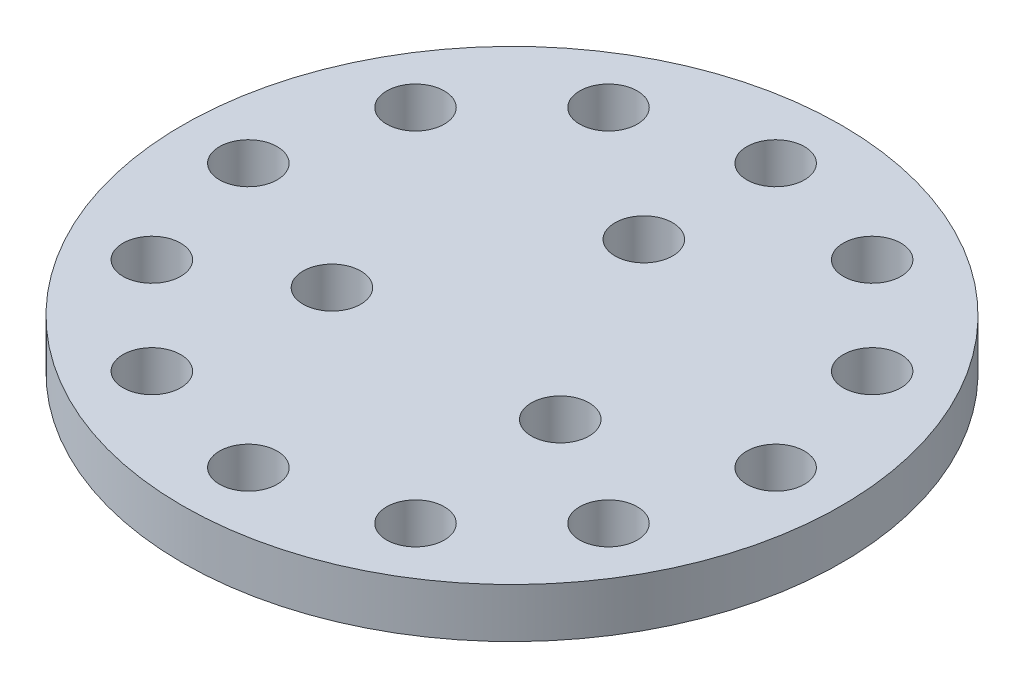
SolidWorks part; units mm, degrees
ref_plane "Plano frontal" through (0, 0, 0) normal (0, 0, 1) x (1, 0, 0)
ref_plane "Plano superior" through (0, 0, 0) normal (0, 1, 0) x (1, 0, 0)
ref_plane "Plano direito" through (0, 0, 0) normal (1, 0, 0) x (0, 0, -1)
sketch "Esboço1" plane through (0, 0, 0) normal (0, 1, 0) x (1, 0, 0)
  circle A0 centre (0, 0) radius 20
  circle A2 centre (-8, 13.8564) radius 1.75
  circle A3 centre (-13.8564, 8) radius 1.75
  circle A4 centre (-16, 0) radius 1.75
  circle A5 centre (-13.8564, -8) radius 1.75
  circle A6 centre (-8, -13.8564) radius 1.75
  circle A7 centre (8, -13.8564) radius 1.75
  circle A8 centre (0, -16) radius 1.75
  circle A9 centre (13.8564, -8) radius 1.75
  circle A10 centre (16, 0) radius 1.75
  circle A11 centre (13.8564, 8) radius 1.75
  circle A12 centre (8, 13.8564) radius 1.75
  circle A13 centre (0, 16) radius 1.75
  circle A14 centre (0, 8) radius 1.75
  circle A15 centre (-6.9282, -4) radius 1.75
  circle A16 centre (6.9282, -4) radius 1.75
extrude "Ressalto-extrusão1" add sketch "Esboço1" along normal blind 3
